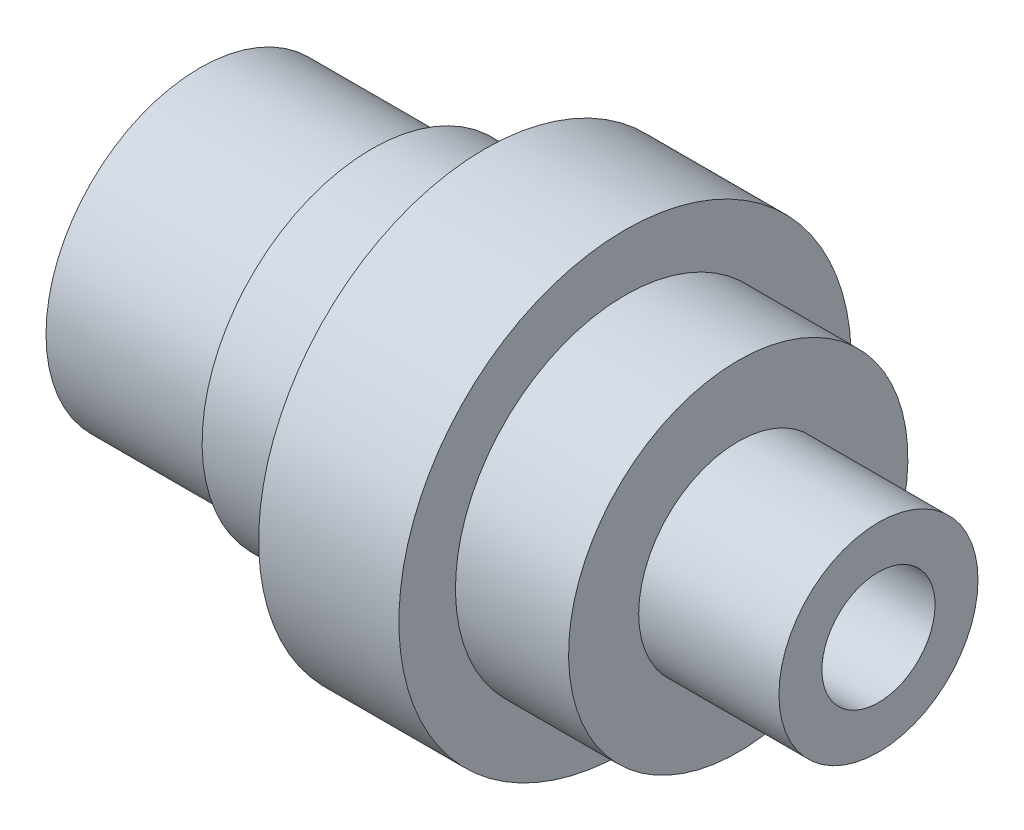
SolidWorks part; units mm, degrees
ref_plane "Front Plane" through (0, 0, 0) normal (0, 0, 1) x (1, 0, 0)
ref_plane "Top Plane" through (0, 0, 0) normal (0, 1, 0) x (1, 0, 0)
ref_plane "Right Plane" through (0, 0, 0) normal (1, 0, 0) x (0, 0, -1)
sketch "Sketch1" plane through (0, 0, 0) normal (0, 0, 1) x (1, 0, 0)
  line L0 (0, 0) -> (0, 8.636)
  line L1 (0, 8.636) -> (9.652, 8.636)
  line L2 (9.652, 8.636) -> (9.652, 9.525)
  line L3 (9.652, 9.525) -> (16.002, 9.525)
  line L4 (16.002, 9.525) -> (16.002, 12.7)
  line L5 (16.002, 12.7) -> (23.876, 12.7)
  line L6 (23.876, 12.7) -> (23.876, 9.525)
  line L7 (23.876, 9.525) -> (30.226, 9.525)
  line L8 (30.226, 9.525) -> (30.226, 5.588)
  line L9 (30.226, 5.588) -> (38.1, 5.588)
  line L10 (38.1, 5.588) -> (38.1, 0)
  line L11 (38.1, 0) -> (0, 0)
  line L12 (38.1, 3.175) -> (0, 3.175)
  line L13 (38.1, 0) -> (38.1, 3.175)
  dimension "D1" = 9.652
  dimension "D2" = 6.35
  dimension "D3" = 7.874
  dimension "D4" = 6.35
  dimension "D5" = 7.874
  dimension "D6" = 3.937
  dimension "D7" = 3.175
  dimension "D8" = 3.175
  dimension "D9" = 0.889
  dimension "D10" = 8.636
  dimension "D11" = 3.175
revolve "Revolve1" add sketch "Sketch1" angle 360 about L11
